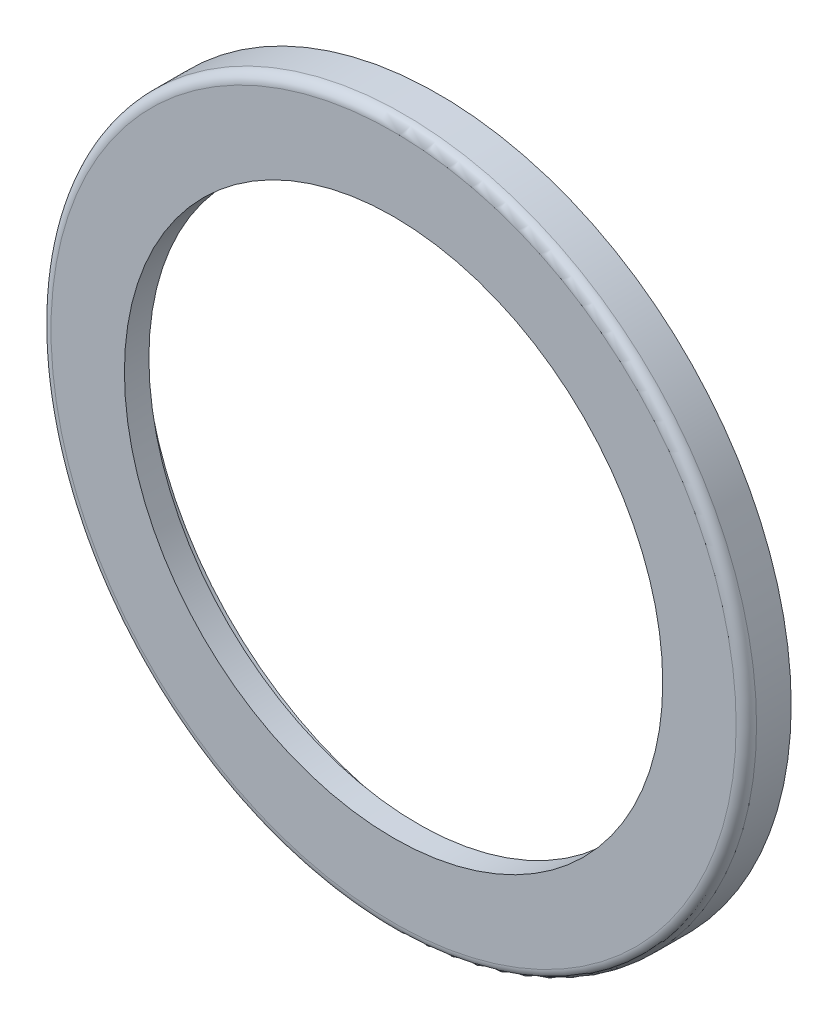
SolidWorks part; units mm, degrees
ref_plane "前视基准面" through (0, 0, 0) normal (0, 0, 1) x (1, 0, 0)
ref_plane "上视基准面" through (0, 0, 0) normal (0, 1, 0) x (1, 0, 0)
ref_plane "右视基准面" through (0, 0, 0) normal (1, 0, 0) x (0, 0, -1)
sketch "草图1" plane through (0, 0, 0) normal (0, 0, 1) x (1, 0, 0)
  circle A0 centre (0, 0) radius 17.3
  circle A1 centre (0, 0) radius 13.2
  dimension "D1" = 34.6
  dimension "D2" = 26.4
extrude "凸台-拉伸1" add sketch "草图1" along normal blind 2.2
sketch "草图2" plane through (0, 0, 0) normal (0, 0, -1) x (-1, 0, 0)
  circle A0 centre (0, 0) radius 14.3941
extrude "切除-拉伸1" cut sketch "草图2" against normal blind 1
sketch "草图3" plane through (0, 0, 0) normal (0, 0, -1) x (-1, 0, 0)
  line L0 (0, 0) -> (0, 19.0924) construction
  line L1 (-2.6421, 14.9861) -> (-2.8636, 16.2427)
  line L2 (2.6421, 14.9861) -> (2.8636, 16.2427)
  line L3 (10.9461, 10.571) -> (11.8639, 11.4574)
  line L4 (6.6711, 13.677) -> (7.2305, 14.8238)
  line L5 (15.0691, 2.1182) -> (16.3326, 2.2958)
  line L6 (13.4362, 7.1437) -> (14.5628, 7.7427)
  line L7 (13.4362, -7.1437) -> (14.5628, -7.7427)
  line L8 (15.0691, -2.1182) -> (16.3326, -2.2958)
  line L9 (6.6711, -13.677) -> (7.2305, -14.8238)
  line L10 (10.9461, -10.571) -> (11.8639, -11.4574)
  line L11 (-2.6421, -14.9861) -> (-2.8636, -16.2427)
  line L12 (2.6421, -14.9861) -> (2.8636, -16.2427)
  line L13 (-10.9461, -10.571) -> (-11.8639, -11.4574)
  line L14 (-6.6711, -13.677) -> (-7.2305, -14.8238)
  line L15 (-15.0691, -2.1182) -> (-16.3326, -2.2958)
  line L16 (-13.4362, -7.1437) -> (-14.5628, -7.7427)
  line L17 (-13.4362, 7.1437) -> (-14.5628, 7.7427)
  line L18 (-15.0691, 2.1182) -> (-16.3326, 2.2958)
  line L19 (-6.6711, 13.677) -> (-7.2305, 14.8238)
  line L20 (-10.9461, 10.571) -> (-11.8639, 11.4574)
  arc A0 (2.8636, 16.2427) -> (-2.8636, 16.2427) centre (0, 0) ccw
  arc A1 (2.6421, 14.9861) -> (-2.6421, 14.9861) centre (0, 0) ccw
  arc A2 (10.9461, 10.571) -> (6.6711, 13.677) centre (0, 0) ccw
  arc A3 (11.8639, 11.4574) -> (7.2305, 14.8238) centre (0, 0) ccw
  arc A4 (15.0691, 2.1182) -> (13.4362, 7.1437) centre (0, 0) ccw
  arc A5 (16.3326, 2.2958) -> (14.5628, 7.7427) centre (0, 0) ccw
  arc A6 (13.4362, -7.1437) -> (15.0691, -2.1182) centre (0, 0) ccw
  arc A7 (14.5628, -7.7427) -> (16.3326, -2.2958) centre (0, 0) ccw
  arc A8 (6.6711, -13.677) -> (10.9461, -10.571) centre (0, 0) ccw
  arc A9 (7.2305, -14.8238) -> (11.8639, -11.4574) centre (0, 0) ccw
  arc A10 (-2.6421, -14.9861) -> (2.6421, -14.9861) centre (0, 0) ccw
  arc A11 (-2.8636, -16.2427) -> (2.8636, -16.2427) centre (0, 0) ccw
  arc A12 (-10.9461, -10.571) -> (-6.6711, -13.677) centre (0, 0) ccw
  arc A13 (-11.8639, -11.4574) -> (-7.2305, -14.8238) centre (0, 0) ccw
  arc A14 (-15.0691, -2.1182) -> (-13.4362, -7.1437) centre (0, 0) ccw
  arc A15 (-16.3326, -2.2958) -> (-14.5628, -7.7427) centre (0, 0) ccw
  arc A16 (-13.4362, 7.1437) -> (-15.0691, 2.1182) centre (0, 0) ccw
  arc A17 (-14.5628, 7.7427) -> (-16.3326, 2.2958) centre (0, 0) ccw
  arc A18 (-6.6711, 13.677) -> (-10.9461, 10.571) centre (0, 0) ccw
  arc A19 (-7.2305, 14.8238) -> (-11.8639, 11.4574) centre (0, 0) ccw
  dimension "D1" = 10
extrude "切除-拉伸2" cut sketch "草图3" against normal blind 1
fillet "圆角1" radius 0.5 1 edges at (17.3, 0, 2.2)
